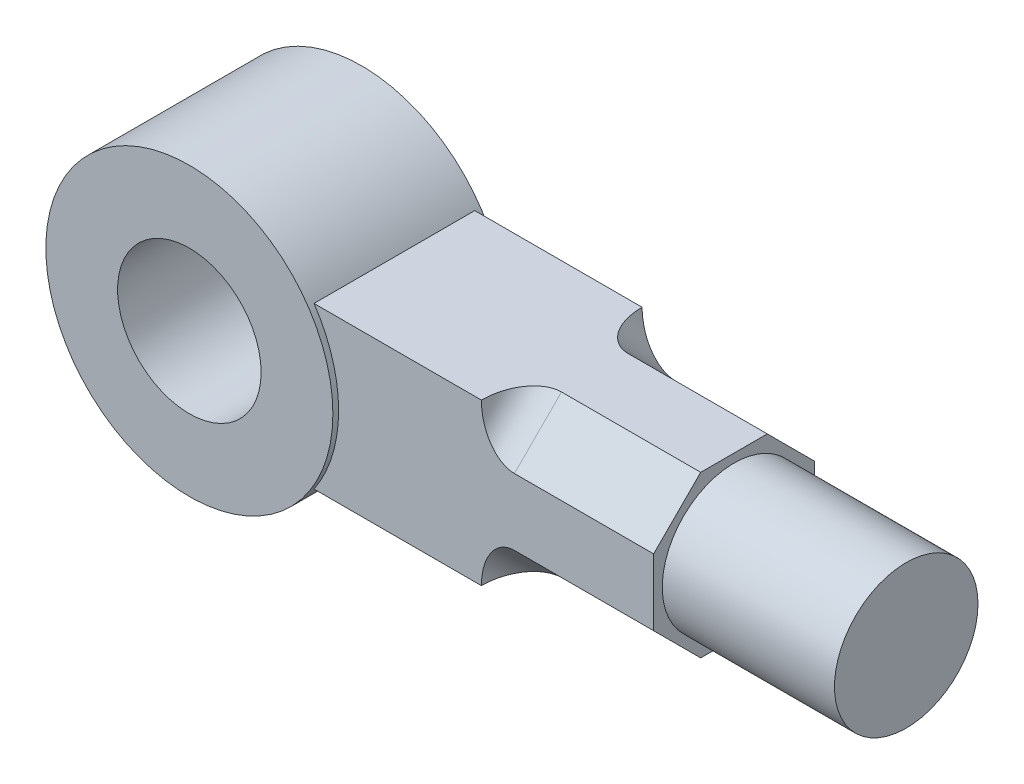
SolidWorks part; units mm, degrees
ref_plane "Front Plane" through (0, 0, 0) normal (0, 0, 1) x (1, 0, 0)
ref_plane "Top Plane" through (0, 0, 0) normal (0, 1, 0) x (1, 0, 0)
ref_plane "Right Plane" through (0, 0, 0) normal (1, 0, 0) x (0, 0, -1)
sketch "Sketch1" plane through (0, 0, 0) normal (0, 0, 1) x (1, 0, 0)
  circle A0 centre (0, 0) radius 12.5
  circle A1 centre (0, 0) radius 25
  dimension "D1" = 25
  dimension "D2" = 50
extrude "Boss-Extrude1" add sketch "Sketch1" along normal blind 30
ref_plane "Plane1" through (0, 0, 15) normal (0, 0, -1) x (-1, 0, 0)
sketch "Sketch2" plane through (0, 0, 15) normal (0, 0, -1) x (-1, 0, 0)
  line L0 (-49.8702, 0) -> (-50, 0) construction
  line L1 (-20.7123, 14) -> (-49.8702, 14)
  line L2 (-20.7123, -14) -> (-49.8702, -14)
  line L3 (0, 14) -> (-79.0281, 14) construction
  line L4 (0, 0) -> (-79.0281, 0) construction
  line L5 (0, -14) -> (-79.0281, -14) construction
  line L6 (-49.8702, 0) -> (-50, 0)
  line L7 (-49.8702, 14) -> (-49.8702, -14)
  arc A0 (-20.7123, 14) -> (-20.7123, -14) centre (0, 0) ccw
  dimension "D3" = 50
  dimension "D1" = 14
  dimension "D2" = 14
extrude "Boss-Extrude2" add sketch "Sketch2" along normal mid plane 28 contours A0 L1 L7 L2
sketch "Sketch6" plane through (49.8702, 0, 0) normal (1, 0, 0) x (0, 0, -1)
  line L0 (-15, 14) -> (-15, -14) construction
  line L1 (-1, 14) -> (-29, 14) construction
  line L2 (-1, -14) -> (-29, -14) construction
  line L3 (-1, 14) -> (-29, 14) construction
  line L4 (-9.201, 14) -> (-20.799, 14)
  line L5 (-20.799, 14) -> (-29, 5.799)
  line L6 (-29, 5.799) -> (-29, -5.799)
  line L7 (-29, -5.799) -> (-20.799, -14)
  line L8 (-20.799, -14) -> (-9.201, -14)
  line L9 (-9.201, -14) -> (-1, -5.799)
  line L10 (-1, -5.799) -> (-1, 5.799)
  line L11 (-1, 5.799) -> (-9.201, 14)
  line L12 (-1, 14) -> (-1, -14) construction
  line L13 (-29, 14) -> (-29, -14) construction
  line L14 (-1, -14) -> (-29, -14) construction
  circle A0 centre (-15, 0) radius 14 construction
extrude "Boss-Extrude5" add sketch "Sketch6" along normal blind 30 contours L4 L5 L6 L7 L8 L9 L10 L11
fillet "Fillet6" radius 5.75 1 edges at (49.8702, 9.8995, 24.8995)
fillet "Fillet7" radius 5.75 1 edges at (49.8702, 9.8995, 5.1005)
fillet "Fillet8" radius 5.75 1 edges at (49.8702, -9.8995, 24.8995)
fillet "Fillet9" radius 5.75 1 edges at (49.8702, -9.8995, 5.1005)
sketch "Sketch7" plane through (79.8702, 0, 0) normal (1, 0, 0) x (0, 0, -1)
  line L0 (-15, 14) -> (-15, -14) construction
  line L1 (-1, 14) -> (-29, 14) construction
  line L2 (-20.799, -14) -> (-9.201, -14) construction
  circle A0 centre (-15, 0) radius 12.5
  dimension "D1" = 25
extrude "Boss-Extrude6" add sketch "Sketch7" along normal blind 30 contours A0
